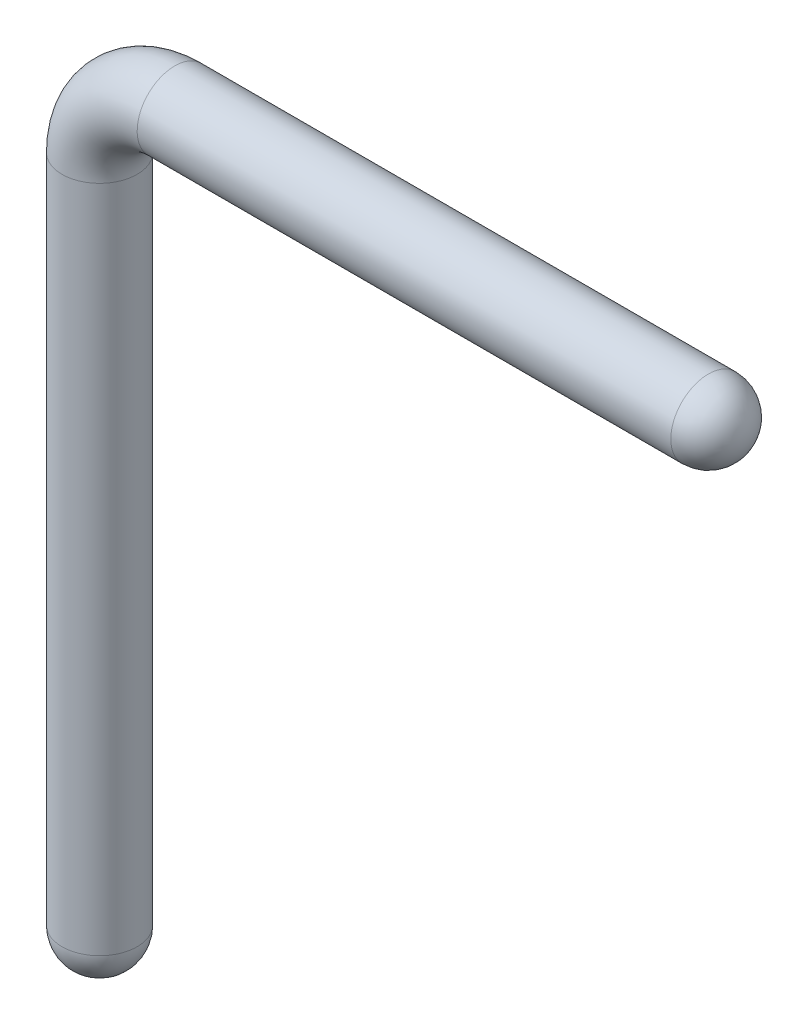
SolidWorks part; units mm, degrees
ref_plane "정면" through (0, 0, 0) normal (0, 0, 1) x (1, 0, 0)
ref_plane "윗면" through (0, 0, 0) normal (0, 1, 0) x (1, 0, 0)
ref_plane "우측면" through (0, 0, 0) normal (1, 0, 0) x (0, 0, -1)
sketch "스케치1" plane through (0, 0, 0) normal (0, 0, 1) x (1, 0, 0)
  line L0 (0, 0) -> (0, 4.7)
  line L1 (0.5, 5.2) -> (4.3, 5.2)
  line L2 (0.5, 5.2) -> (0.5, 4.7) construction
  line L3 (0.5, 4.7) -> (0, 4.7) construction
  arc A1 (0.5, 5.2) -> (0, 4.7) centre (0.5, 4.7) ccw
  dimension "D1" = 4.3
  dimension "D2" = 5.2
  dimension "D3" = 0.5
sketch "스케치2" plane through (0, 0, 0) normal (0, 1, 0) x (1, 0, 0)
  circle A0 centre (0, 0) radius 0.25
  dimension "D1" = 0.5
sweep "스윕3" add profiles "스케치2" path "스케치1"
fillet "필렛1" radius 0.25 2 edges at (4.3, 5.2, 0.25) (0, 0, 0.25)
